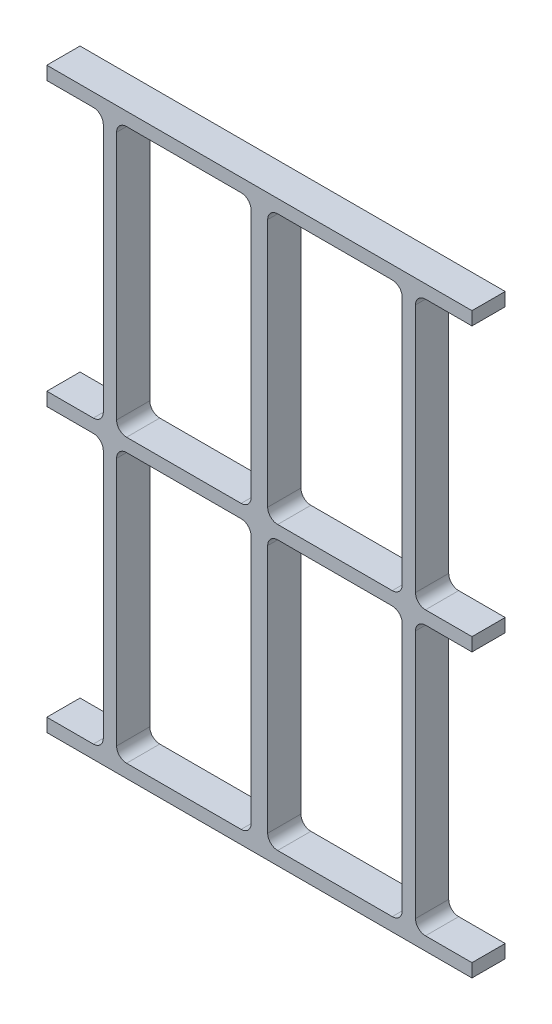
SolidWorks part; units mm, degrees
ref_plane "Front Plane" through (0, 0, 0) normal (0, 0, 1) x (1, 0, 0)
ref_plane "Top Plane" through (0, 0, 0) normal (0, 1, 0) x (1, 0, 0)
ref_plane "Right Plane" through (0, 0, 0) normal (1, 0, 0) x (0, 0, -1)
sketch "Sketch1" plane through (0, 0, 0) normal (0, 0, 1) x (1, 0, 0)
  line L0 (-64, 125.5) -> (-47, 125.5)
  line L5 (-64, 129.5) -> (0, 129.5)
  line L6 (0, -79) -> (0, -44.5) construction
  line L7 (4.5, -79) -> (-4.5, -79) construction
  line L8 (-4.5, 164) -> (4.5, 164) construction
  line L9 (-54, 42.5) -> (-45, 42.5) construction
  line L11 (-54, -42.5) -> (0, -42.5) construction
  line L13 (-43, 44.5) -> (-43, 125.5)
  line L14 (-54, 127.5) -> (0, 127.5) construction
  line L16 (-47, 44.5) -> (-47, 125.5)
  line L17 (-64, 40.5) -> (-47, 40.5)
  line L18 (-45, 42.5) -> (-45, 127.5) construction
  line L19 (-45, 42.5) -> (-45, -42.5) construction
  line L20 (0, 129.5) -> (0, 164) construction
  line L21 (-64, 44.5) -> (-47, 44.5)
  line L22 (-47, 40.5) -> (-47, -40.5)
  line L23 (-43, 40.5) -> (-43, -40.5)
  line L24 (-64, -44.5) -> (0, -44.5)
  line L25 (-64, -40.5) -> (-47, -40.5)
  line L29 (-43, 125.5) -> (-2.5, 125.5)
  line L30 (-54, 40.5) -> (-45, 40.5) construction
  line L31 (-47, 42.5) -> (-47, 127.5) construction
  line L32 (-43, -40.5) -> (-2.5, -40.5)
  line L34 (-54, 125.5) -> (0, 125.5) construction
  line L35 (-43, 42.5) -> (-43, 127.5) construction
  line L39 (45, 42.5) -> (45, -42.5) construction
  line L40 (45, 42.5) -> (45, 127.5) construction
  line L41 (54, 127.5) -> (0, 127.5) construction
  line L42 (54, -42.5) -> (0, -42.5) construction
  line L43 (54, 42.5) -> (45, 42.5) construction
  line L47 (64, -40.5) -> (47, -40.5)
  line L48 (64, -44.5) -> (0, -44.5)
  line L49 (43, 40.5) -> (43, -40.5)
  line L50 (47, 40.5) -> (47, -40.5)
  line L51 (64, 44.5) -> (47, 44.5)
  line L52 (64, 40.5) -> (47, 40.5)
  line L53 (47, 44.5) -> (47, 125.5)
  line L54 (43, 44.5) -> (43, 125.5)
  line L55 (64, 129.5) -> (0, 129.5)
  line L56 (64, 125.5) -> (47, 125.5)
  line L57 (-64, 129.5) -> (-64, 125.5)
  line L58 (64, -44.5) -> (64, -40.5)
  line L59 (64, 125.5) -> (64, 129.5)
  line L60 (64, 40.5) -> (64, 44.5)
  line L61 (-64, -40.5) -> (-64, -44.5)
  line L62 (-64, 44.5) -> (-64, 40.5)
  line L63 (2.5, 44.5) -> (43, 44.5)
  line L64 (-43, 40.5) -> (-2.5, 40.5)
  line L65 (-43, 44.5) -> (-2.5, 44.5)
  line L67 (-2.5, 125.5) -> (-2.5, 44.5)
  line L68 (2.5, 125.5) -> (43, 125.5)
  line L69 (-2.5, 40.5) -> (-2.5, -40.5)
  line L70 (2.5, 40.5) -> (43, 40.5)
  line L71 (2.5, 44.5) -> (2.5, 125.5)
  line L73 (2.5, -40.5) -> (43, -40.5)
  line L74 (2.5, -40.5) -> (2.5, 40.5)
  point P9 (0, 0)
  point P46 (0, 0)
  dimension "D3" = 2
extrude "Boss-Extrude1" add sketch "Sketch1" along normal blind 10
fillet "Fillet1" radius 3 24 edges at (47, -40.5, 5) (47, 44.5, 5) (47, 40.5, 5) (47, 125.5, 5) (-47, 125.5, 5) (-43, 125.5, 5) (-43, 44.5, 5) (-43, 40.5, 5) (-47, 40.5, 5) (-47, 44.5, 5) (-47, -40.5, 5) (-43, -40.5, 5) (43, 40.5, 5) (43, 44.5, 5) (43, 125.5, 5) (-2.5, 125.5, 5) (2.5, 125.5, 5) (2.5, 40.5, 5) (-2.5, 40.5, 5) (-2.5, 44.5, 5) (2.5, 44.5, 5) (43, -40.5, 5) (-2.5, -40.5, 5) (2.5, -40.5, 5)
